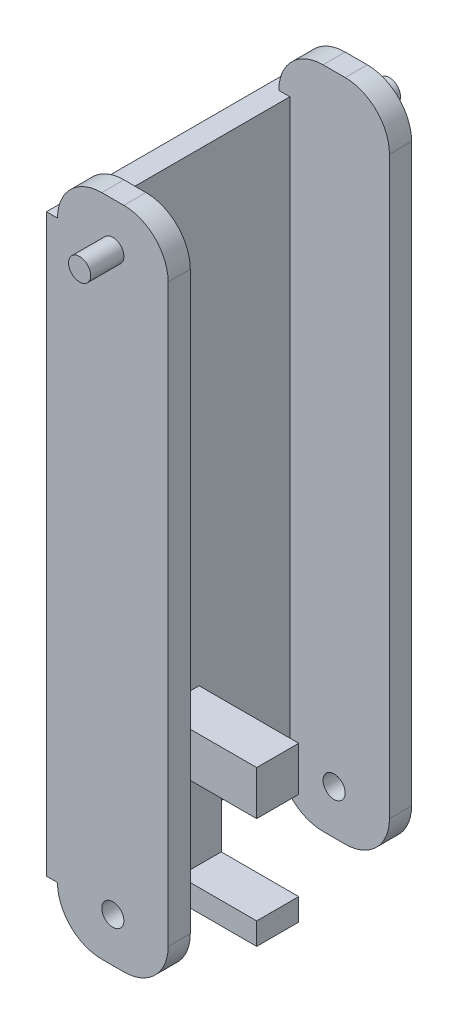
SolidWorks part; units mm, degrees
ref_plane "Front Plane" through (0, 0, 0) normal (0, 0, 1) x (1, 0, 0)
ref_plane "Top Plane" through (0, 0, 0) normal (0, 1, 0) x (1, 0, 0)
ref_plane "Right Plane" through (0, 0, 0) normal (1, 0, 0) x (0, 0, -1)
sketch "Sketch1" plane through (0, 0, 0) normal (0, 0, 1) x (1, 0, 0)
  line L0 (0, 7.8092) -> (0, -7.5836) construction
  line L1 (-16.5434, 0) -> (17.7066, 0) construction
  line L2 (-5, -20) -> (5, -20)
  line L6 (0, 7.8092) -> (0, 18.1168) construction
  line L7 (-25, 0) -> (-25, 260)
  line L8 (-5, 280) -> (5, 280)
  line L9 (25, 260) -> (25, 0)
  line L10 (0, 332.7621) -> (0, -24.8778) construction
  arc A0 (5, -20) -> (25, 0) centre (5, 0) ccw
  arc A1 (-5, -20) -> (-25, 0) centre (-5, 0) cw
  circle A2 centre (0, 0) radius 5
  arc A3 (5, 280) -> (25, 260) centre (5, 260) cw
  arc A4 (-25, 260) -> (-5, 280) centre (-5, 260) cw
  point P14 (25, -20)
  point P17 (-25, -20)
  point P22 (25, 280)
  dimension "D4" = 20
  dimension "D5" = 20
  dimension "D6" = 20
  dimension "D1" = 50
  dimension "D2" = 25
  dimension "D3" = 300
extrude "Boss-Extrude1" add sketch "Sketch1" along normal blind 10
sketch "Sketch2" plane through (0, 0, 10) normal (0, 0, 1) x (1, 0, 0)
  line L0 (0, 310.2932) -> (0, -54.3198) construction
  line L1 (5, 280) -> (-5, 280) construction
  circle A1 centre (0, 260) radius 5
  dimension "D1" = 20
  dimension "D2" = 10
extrude "Boss-Extrude2" add sketch "Sketch2" along normal blind 15
sketch "Sketch3" plane through (0, 0, 0) normal (0, 0, -1) x (-1, 0, 0)
  line L0 (0, -108.7365) -> (0, 392.6868) construction
  line L1 (25, 0) -> (20, 0)
  line L2 (20, 0) -> (20, 260)
  line L3 (20, 260) -> (25, 260)
  line L4 (25, 260) -> (25, 0)
  dimension "D1" = 260
  dimension "D2" = 260
  dimension "D3" = 5
  dimension "D4" = 20
extrude "Boss-Extrude3" add sketch "Sketch3" along normal blind 45
mirror "Mirror1" about plane through (0, 0, -45) normal (0, 0, 1) of "Boss-Extrude3", "Boss-Extrude2", "Boss-Extrude1"
sketch "Sketch8" plane through (0, 0, 0) normal (0, -1, 0) x (1, 0, 0)
  line L0 (-25, -30) -> (-20, -30)
  line L2 (-25, -90) -> (-25, 0) construction
  line L3 (-20, -90) -> (-20, 0) construction
  line L4 (-20, -30) -> (-20, -49)
  line L5 (-20, -49) -> (-25, -49)
  line L6 (-25, -49) -> (-25, -30)
  line L7 (-20, 0) -> (-25, 0) construction
  line L8 (-5, -90) -> (-25, -90) construction
  dimension "D1" = 30
  dimension "D2" = 19
  dimension "D3" = 41
extrude "Boss-Extrude4" add sketch "Sketch8" along normal blind 20
sketch "Sketch9" plane through (-20, 0, 0) normal (1, 0, 0) x (0, 0, -1)
  line L0 (30, -20) -> (30, -10)
  line L1 (30, -20) -> (30, 0) construction
  line L2 (30, -10) -> (49, -10)
  line L3 (49, -20) -> (49, 0) construction
  line L4 (49, -10) -> (49, -20)
  line L5 (49, -20) -> (30, -20)
  line L6 (30, 286.5383) -> (30, -36.1632) construction
  line L7 (49, 286.5383) -> (49, -36.1632) construction
  line L8 (49, 30) -> (30, 30)
  line L9 (30, 30) -> (30, 50)
  line L10 (30, 50) -> (49, 50)
  line L11 (49, 50) -> (49, 30)
  dimension "D1" = 10
  dimension "D2" = 40
  dimension "D3" = 20
extrude "Boss-Extrude5" add sketch "Sketch9" along normal blind 45
sketch "Sketch10" plane through (-20, 0, 0) normal (1, 0, 0) x (0, 0, -1)
  line L0 (30, 30) -> (30, -10)
  line L1 (30, -10) -> (49, -10)
  line L2 (49, -10) -> (49, 30)
  line L3 (49, 30) -> (30, 30)
extrude "Boss-Extrude6" add sketch "Sketch10" along normal blind 10
sketch "Sketch11" plane through (-25, 0, 0) normal (-1, 0, 0) x (0, 0, 1)
  line L0 (10, 0) -> (-30, 0)
  line L1 (-30, 0) -> (-30, -20)
  line L2 (-30, -20) -> (-49, -20)
  line L3 (-49, -20) -> (-49, 0)
  line L4 (-49, 0) -> (-100, 0)
  line L5 (-100, 0) -> (-100, 260)
  line L6 (-100, 265) -> (-100, 255) construction
  line L7 (-100, 260) -> (10, 260)
  line L8 (10, 255) -> (10, 265) construction
  line L9 (10, 260) -> (10, 0)
extrude "Boss-Extrude7" add sketch "Sketch11" along normal blind 5
